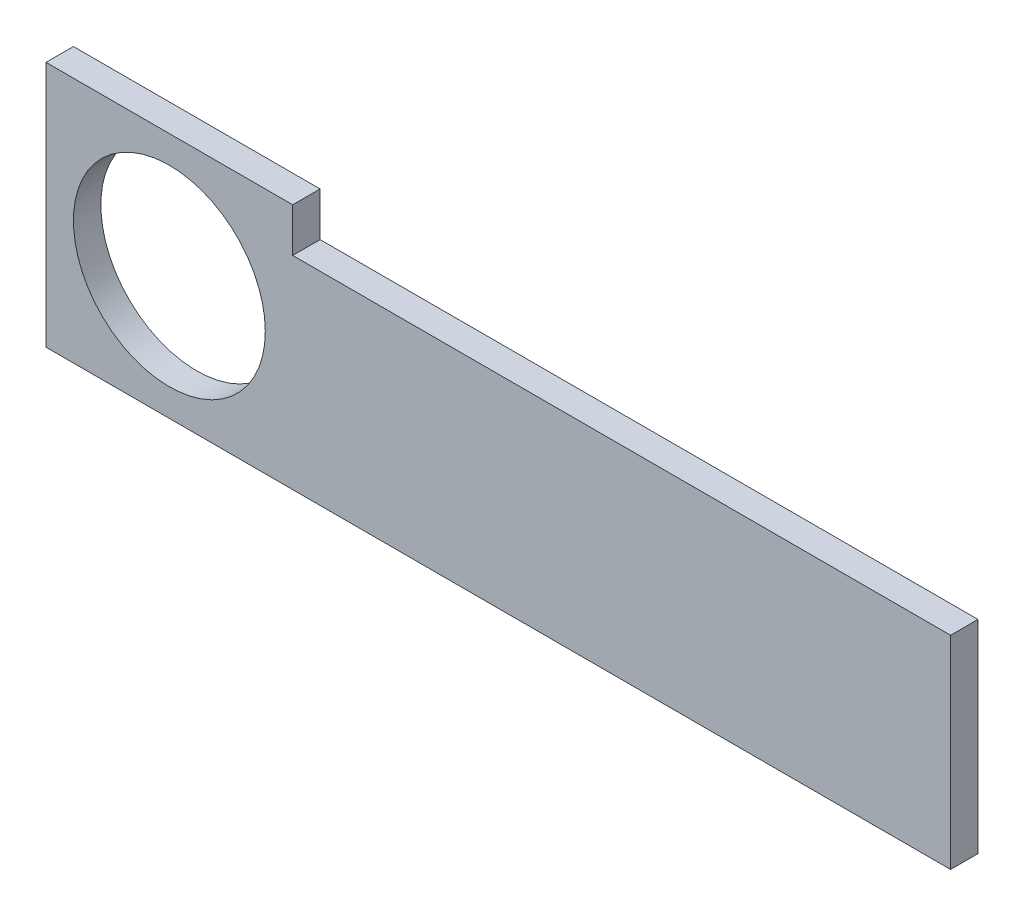
SolidWorks part; units mm, degrees
material "Plain Carbon Steel"
ref_plane "Front Plane" through (0, 0, 0) normal (0, 0, 1) x (1, 0, 0)
ref_plane "Top Plane" through (0, 0, 0) normal (0, 1, 0) x (1, 0, 0)
ref_plane "Right Plane" through (0, 0, 0) normal (1, 0, 0) x (0, 0, -1)
sketch "Sketch1" plane through (0, 0, 0) normal (0, 0, 1) x (1, 0, 0)
  line L0 (-33.3006, 96.1433) -> (-327.3006, 96.1433) construction
  line L1 (-100.3006, 96.1433) -> (-340.3006, 96.1433)
  line L2 (-100.3006, 96.1433) -> (-100.3006, 22.1433)
  line L3 (-100.3006, 22.1433) -> (-430.3006, 22.1433)
  line L4 (-430.3006, 96.1433) -> (-430.3006, 22.1433)
  line L5 (-327.3006, 22.1433) -> (-33.3006, 22.1433) construction
  line L6 (-100.3006, 99.1433) -> (-100.3006, 29.1433) construction
  line L8 (-340.3006, 96.1433) -> (-340.3006, 112.1433)
  line L9 (-340.3006, 112.1433) -> (-430.3006, 112.1433)
  line L10 (-430.3006, 112.1433) -> (-430.3006, 96.1433)
  line L11 (-330.3006, 99.1433) -> (-330.3006, 29.1433) construction
  line L12 (-340.3006, 112.1433) -> (-340.3006, 22.1433) construction
  line L13 (-430.3006, 67.1433) -> (-340.3006, 67.1433) construction
  line L14 (-385.3006, 112.1433) -> (-385.3006, 22.1433) construction
  line L15 (-385.3006, 67.1433) -> (-417.1204, 98.9631) construction
  line L16 (-385.3006, 67.1433) -> (-353.4808, 98.9631) construction
  line L17 (-385.3006, 67.1433) -> (-353.4808, 35.3235) construction
  line L18 (-385.3006, 67.1433) -> (-417.1204, 35.3235) construction
  circle A0 centre (-385.3006, 67.1433) radius 45 construction
  point P15 (-340.3006, 67.1433)
  point P21 (-385.3006, 67.1433)
  point P23 (-385.3006, 67.1433)
  point P32 (-385.3006, 67.1433)
  dimension "D1" = 90
  dimension "D2" = 10
  dimension "D3" = 90
  dimension "D5" = 45
  dimension "D6" = 4
extrude "Boss-Extrude1" add sketch "Sketch1" along normal blind 10
sketch "Sketch2" plane through (0, 0, 10) normal (0, 0, 1) x (1, 0, 0)
  circle A0 centre (-385.3006, 67.1433) radius 35
  dimension "D1" = 70
extrude "Cut-Extrude1" cut sketch "Sketch2" against normal through all
